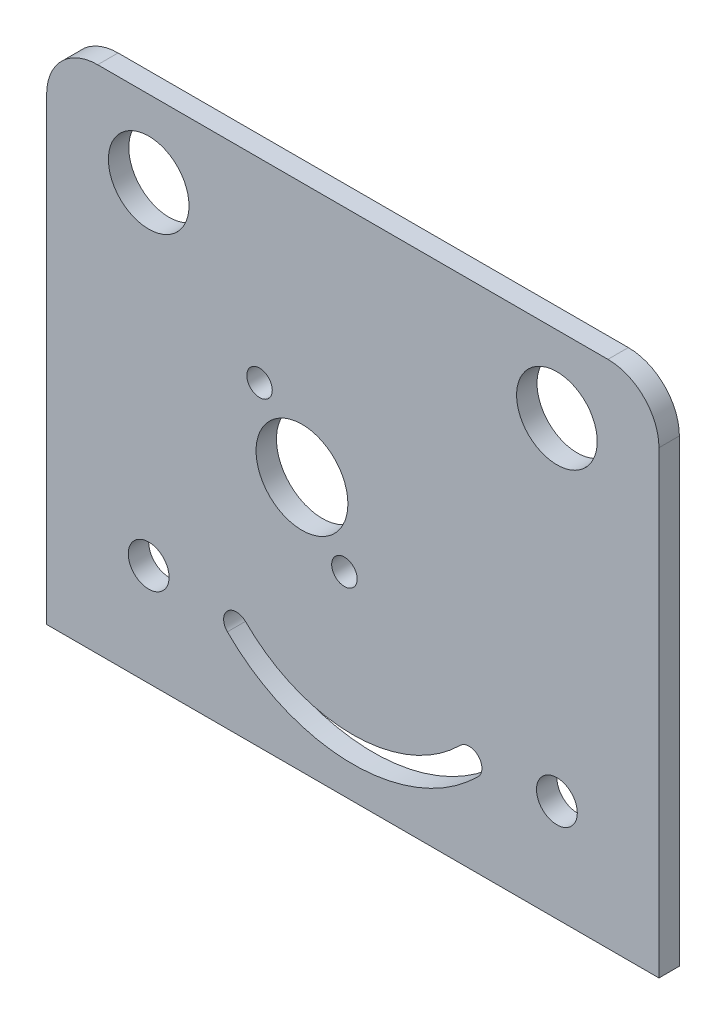
SolidWorks part; units mm, degrees
ref_plane "Front Plane" through (0, 0, 0) normal (0, 0, 1) x (1, 0, 0)
ref_plane "Top Plane" through (0, 0, 0) normal (0, 1, 0) x (1, 0, 0)
ref_plane "Right Plane" through (0, 0, 0) normal (1, 0, 0) x (0, 0, -1)
sketch "Sketch1" plane through (0, 0, 0) normal (0, 0, 1) x (1, 0, 0)
  line L0 (60, 100) -> (60, -32.1299) construction
  line L1 (0, 0) -> (120, 0)
  line L2 (0, 0) -> (0, 90)
  line L3 (10, 100) -> (110, 100)
  line L4 (120, 0) -> (120, 90)
  line L5 (100, 85) -> (50.04, 50) construction
  line L6 (37.1302, 68.4279) -> (62.9499, 31.5721) construction
  circle A0 centre (100, 85) radius 7.9
  circle A1 centre (20, 85) radius 7.9
  circle A2 centre (100, 85) radius 50 construction
  circle A3 centre (100, 85) radius 61 construction
  circle A4 centre (50.04, 50) radius 13 construction
  circle A5 centre (50.04, 50) radius 22.5 construction
  circle A6 centre (50.04, 50) radius 14.5 construction
  circle A7 centre (50.04, 50) radius 9
  circle A8 centre (58.3597, 38.1243) radius 2.5
  circle A9 centre (41.7203, 61.8757) radius 2.5
  circle A10 centre (100, 20) radius 4
  circle A11 centre (20, 20) radius 4
  arc A12 (110, 100) -> (120, 90) centre (110, 90) cw
  arc A13 (0, 90) -> (10, 100) centre (10, 90) cw
  arc A14 (38.9598, 20) -> (81.0402, 20) centre (60, 41.0402) ccw
  arc A15 (35.4243, 16.4645) -> (84.5757, 16.4645) centre (60, 41.0402) ccw
  arc A16 (81.0402, 20) -> (84.5757, 16.4645) centre (82.8079, 18.2322) cw
  arc A17 (35.4243, 16.4645) -> (38.9598, 20) centre (37.1921, 18.2322) cw
  point P30 (120, 100)
  point P33 (0, 100)
  dimension "D4" = 15.8
  dimension "D7" = 100
  dimension "D8" = 122
  dimension "D9" = 26
  dimension "D10" = 45
  dimension "D11" = 29
  dimension "D12" = 18
  dimension "D13" = 5
  dimension "D14" = 8
  dimension "D15" = 65
  dimension "D17" = 10
  dimension "D1" = 120
  dimension "D2" = 100
  dimension "D3" = 15
  dimension "D5" = 80
  dimension "D6" = 40
  dimension "D16" = 50
  dimension "D18" = 5
extrude "Boss-Extrude1" add sketch "Sketch1" along normal blind 4
